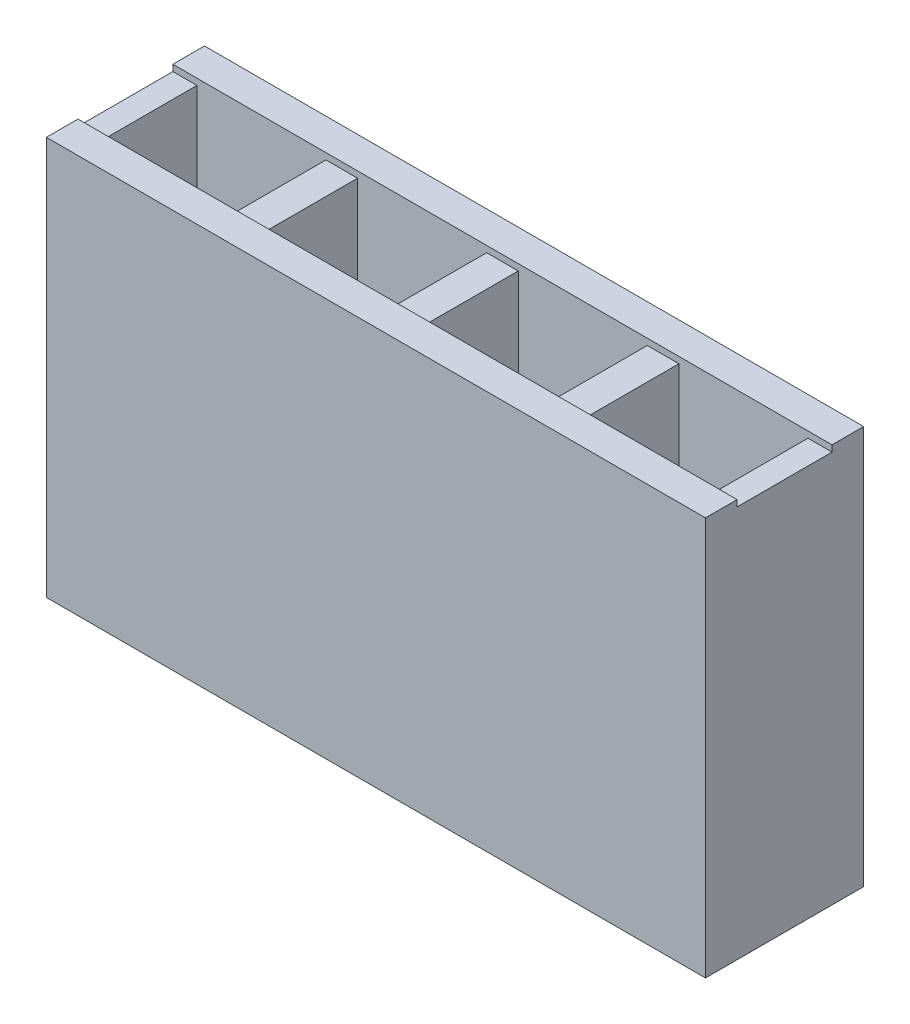
SolidWorks part; units mm, degrees
ref_plane "Front Plane" through (0, 0, 0) normal (0, 0, 1) x (1, 0, 0)
ref_plane "Top Plane" through (0, 0, 0) normal (0, 1, 0) x (1, 0, 0)
ref_plane "Right Plane" through (0, 0, 0) normal (1, 0, 0) x (0, 0, -1)
sketch "Sketch1" plane through (0, 0, 0) normal (0, 1, 0) x (1, 0, 0)
  line L1 (-5.21, -1.25) -> (5.21, -1.25)
  line L2 (-5.21, -1.25) -> (-5.21, 1.25)
  line L3 (-5.21, 1.25) -> (5.21, 1.25)
  line L4 (5.21, -1.25) -> (5.21, 1.25)
  line L5 (-5.21, -1.25) -> (5.21, 1.25) construction
  line L6 (-5.21, 1.25) -> (5.21, -1.25) construction
  point P0 (0, 0)
  dimension "D1" = 2.5
  dimension "D2" = 10.42
extrude "Boss-Extrude1" add sketch "Sketch1" along normal blind 6.2
sketch "Sketch2" plane through (0, 6.2, 0) normal (0, 1, 0) x (1, 0, 0)
  line L0 (-5.21, 1.25) -> (-5.21, -1.25) construction
  line L1 (-4.83, -0.75) -> (-2.79, -0.75)
  line L2 (-4.83, -0.75) -> (-4.83, 0.75)
  line L3 (-4.83, 0.75) -> (-2.79, 0.75)
  line L4 (-2.79, -0.75) -> (-2.79, 0.75)
  line L5 (-4.83, -0.75) -> (-2.79, 0.75) construction
  line L6 (-4.83, 0.75) -> (-2.79, -0.75) construction
  point P0 (-3.81, 0)
  dimension "D1" = 1.4
  dimension "D2" = 2.04
  dimension "D3" = 1.5
extrude "Cut-Extrude1" cut sketch "Sketch2" against normal blind 5.7
sketch "Sketch3" plane through (0, 0, 0) normal (0, -1, 0) x (1, 0, 0)
  line L1 (-4.61, -0.8) -> (-3.01, -0.8)
  line L2 (-4.61, -0.8) -> (-4.61, 0.8)
  line L3 (-4.61, 0.8) -> (-3.01, 0.8)
  line L4 (-3.01, -0.8) -> (-3.01, 0.8)
  line L5 (-4.61, -0.8) -> (-3.01, 0.8) construction
  line L6 (-4.61, 0.8) -> (-3.01, -0.8) construction
  line L7 (-5.21, 1.25) -> (5.21, 1.25) construction
  line L8 (-5.21, -1.25) -> (-5.21, 1.25) construction
  point P0 (-3.81, 0)
  dimension "D1" = 1.6
  dimension "D2" = 1.4
  dimension "D3" = 0.45
extrude "Cut-Extrude2" cut sketch "Sketch3" against normal up to next (0.5 mm away) draft 45
pattern_linear "LPattern1" count 4 spacing 2.54 along (1, 0, 0) of "Cut-Extrude1", "Cut-Extrude2"
sketch "Sketch4" plane through (0, 6.2, 0) normal (0, 1, 0) x (1, 0, 0)
  line L0 (-5.21, 1.25) -> (-5.21, -1.25) construction
  line L1 (5.21, 0.75) -> (-5.21, 0.75)
  line L2 (5.21, 0.75) -> (5.21, 1.25)
  line L3 (5.21, 1.25) -> (-5.21, 1.25)
  line L4 (-5.21, 0.75) -> (-5.21, 1.25)
  line L8 (5.21, -1.25) -> (5.21, 1.25) construction
  line L9 (5.21, 1.25) -> (-5.21, 1.25) construction
  point P9 (0, 0)
extrude "Boss-Extrude2" add sketch "Sketch4" along normal blind 0.1
mirror "Mirror1" about plane through (0, 0, 0) normal (0, 0, 1) of "Boss-Extrude2"
